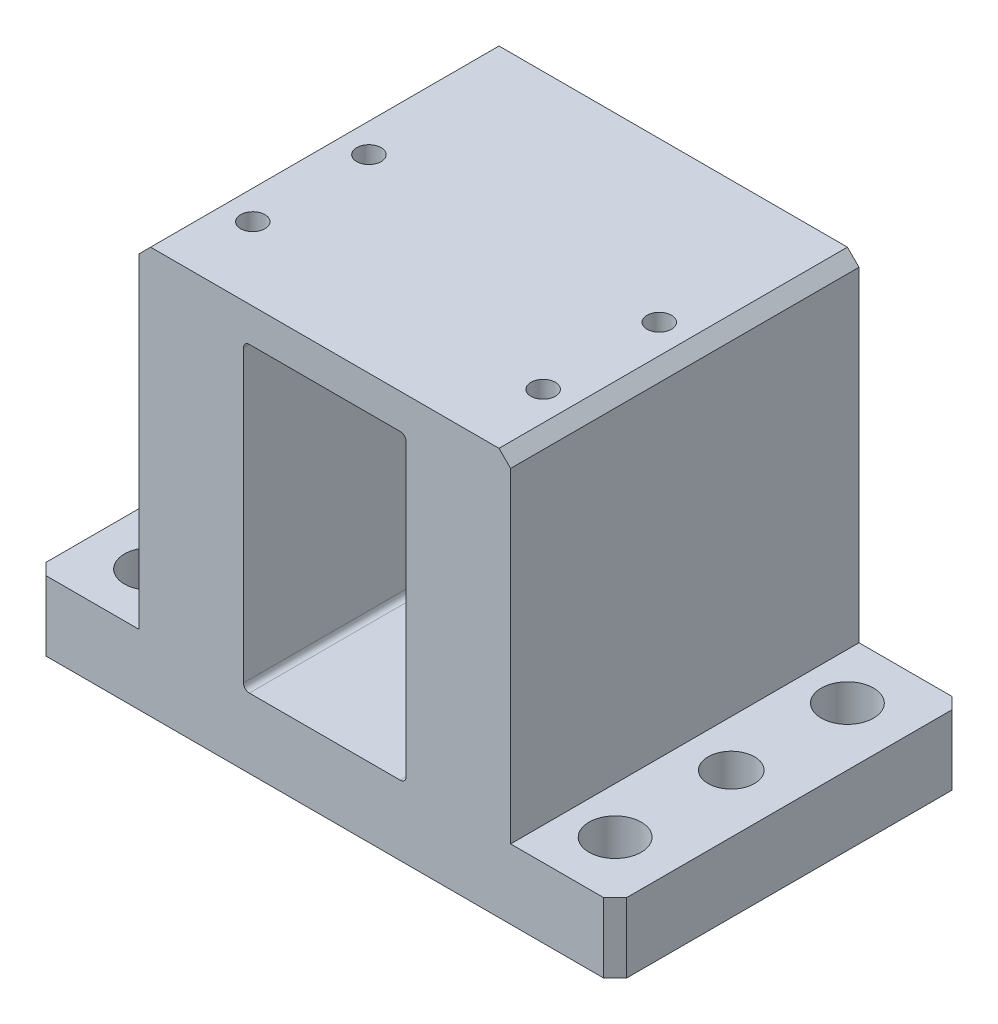
SolidWorks part; units mm, degrees
material "一般碳鋼"
ref_plane "前基準面" through (0, 0, 0) normal (0, 0, 1) x (1, 0, 0)
ref_plane "上基準面" through (0, 0, 0) normal (0, 1, 0) x (1, 0, 0)
ref_plane "右基準面" through (0, 0, 0) normal (1, 0, 0) x (0, 0, -1)
sketch "草圖1" plane through (0, 0, 0) normal (0, 0, 1) x (1, 0, 0)
  line L0 (-50, -35) -> (50, 35) construction
  line L1 (-50, 35) -> (50, 35)
  line L2 (-50, 35) -> (-50, -35)
  line L3 (-50, -35) -> (50, -35)
  line L4 (50, 35) -> (50, -35)
  dimension "D1" = 100
  dimension "D2" = 70
extrude "伸長1" add sketch "草圖1" along normal mid plane 60
sketch "草圖2" plane through (0, 35, 0) normal (0, 1, 0) x (1, 0, 0)
  line L0 (50, 30) -> (-50, 30) construction
  line L1 (32, 30) -> (50, 30)
  line L2 (32, 30) -> (32, -30)
  line L3 (32, -30) -> (50, -30)
  line L4 (50, 30) -> (50, -30)
  line L5 (50, -30) -> (-50, -30) construction
  line L8 (-50, 30) -> (-32, 30)
  line L9 (-50, 30) -> (-50, -30)
  line L10 (-50, -30) -> (-32, -30)
  line L11 (-32, 30) -> (-32, -30)
  dimension "D1" = 18
extrude "除料-伸長1" cut sketch "草圖2" against normal blind 58
hole_wizard "Ø9.0 (9) 直徑孔1" positions "草圖16" profile "草圖15" hole size "Ø9.0" standard "ISO" end condition up to next
sketch "草圖16" plane through (-40, -23, 55) normal (0, 1, 0) x (-1, 0, 0)
  line L0 (-40, -85) -> (-40, -26.4271) construction
  line L2 (-8, -85) -> (10, -85) construction
  point P0 (0, -75)
  point P1 (-80, -75)
  point P13 (-80, -35)
  point P15 (0, -35)
  dimension "D1" = 80
  dimension "D2" = 40
  dimension "D3" = 10
  dimension "D4" = 40
sketch "草圖15" plane through (-40, -23, -20) normal (1, 0, 0) x (0, 0, 1)
  line L0 (0, 0) -> (0, 12)
  line L1 (0, 12) -> (4.5, 12)
  line L2 (4.5, 12) -> (4.5, 0)
  line L5 (4.5, 0) -> (0, 0)
  line L11 (0, -6.35) -> (0, 107.95) construction
  dimension "貫穿孔直徑" = 9
  dimension "貫穿孔深度" = 12
sketch "草圖17" plane through (0, 0, -30) normal (0, 0, -1) x (-1, 0, 0)
  line L0 (0, -13.9769) -> (0, 3.5868) construction
  line L1 (13, -23) -> (-13, -23)
  line L2 (14, -22) -> (14, 28)
  line L3 (13, 29) -> (-13, 29)
  line L4 (-14, -22) -> (-14, 28)
  line L6 (50, -35) -> (-50, -35) construction
  arc A0 (-14, 28) -> (-13, 29) centre (-13, 28) cw
  arc A1 (14, 28) -> (13, 29) centre (13, 28) ccw
  arc A2 (-13, -23) -> (-14, -22) centre (-13, -22) cw
  arc A3 (14, -22) -> (13, -23) centre (13, -22) cw
  dimension "D4" = 1
  dimension "D1" = 28
  dimension "D2" = 12
  dimension "D3" = 52
extrude "除料-伸長2" cut sketch "草圖17" against normal up to next
hole_wizard "Ø8.0 (8) 直徑孔1" positions "草圖19" profile "草圖18" hole size "Ø8.0" standard "ISO" end condition up to next
sketch "草圖19" plane through (20, -23, 5.3254) normal (0, 1, 0) x (-1, 0, 0)
  line L0 (20, 24.6746) -> (20, 19.3491) construction
  line L3 (-30, -5.3254) -> (-22.6983, -5.3254) construction
  line L4 (-30, 24.6746) -> (-30, -35.3254) construction
  point P0 (60, -5.3254)
  point P1 (-20, -5.3254)
  dimension "D1" = 80
  dimension "D2" = 40
sketch "草圖18" plane through (-40, -23, 0) normal (1, 0, 0) x (0, 0, 1)
  line L0 (0, 0) -> (0, 12)
  line L1 (0, 12) -> (4, 12)
  line L2 (4, 12) -> (4, 0)
  line L5 (4, 0) -> (0, 0)
  line L11 (0, -6.35) -> (0, 107.95) construction
  dimension "貫穿孔直徑" = 8
  dimension "貫穿孔深度" = 12
hole_wizard "M5 螺紋孔1" positions "草圖21" profile "草圖20" tap size "M5" standard "GB"
sketch "草圖21" plane through (0, 35, 0) normal (0, 1, 0) x (-1, 0, 0)
  line L0 (0, 30) -> (0, 6.8473) construction
  line L1 (-32, 30) -> (32, 30) construction
  line L3 (-32, 7.4) -> (-17.7433, 7.4) construction
  point P0 (25, 17.4)
  point P1 (-25, 17.4)
  point P3 (-25, -2.6)
  point P5 (25, -2.6)
  dimension "D1" = 20
  dimension "D2" = 50
  dimension "D3" = 22.6
sketch "草圖20" plane through (-25, 35, 17.4) normal (1, 0, 0) x (0, 0, 1)
  line L0 (0, 0) -> (0, 17.2618)
  line L1 (0, 17.2618) -> (2.1, 16)
  line L2 (2.1, 16) -> (2.1, 0)
  line L5 (2.1, 0) -> (0, 0)
  line L10 (0, 17.2618) -> (-2.1, 16) construction
  line L11 (0, -6.35) -> (0, 107.95) construction
  dimension "螺孔鑽直徑" = 4.2
  dimension "螺孔鑽深度" = 16
  dimension "導頭角度" = 118
cosmetic thread "鑽孔螺紋1" parameters "D1"=12, "D2"=5
cosmetic thread "鑽孔螺紋2" parameters "D1"=12, "D2"=5
cosmetic thread "鑽孔螺紋3" parameters "D1"=12, "D2"=5
cosmetic thread "鑽孔螺紋4" parameters "D1"=12, "D2"=5
chamfer "導角1" distance 2 angle 45 6 edges at (-50, -29, -30) (50, -29, -30) (-50, -29, 30) (50, -29, 30) (-32, 35, 0) (32, 35, 0)
